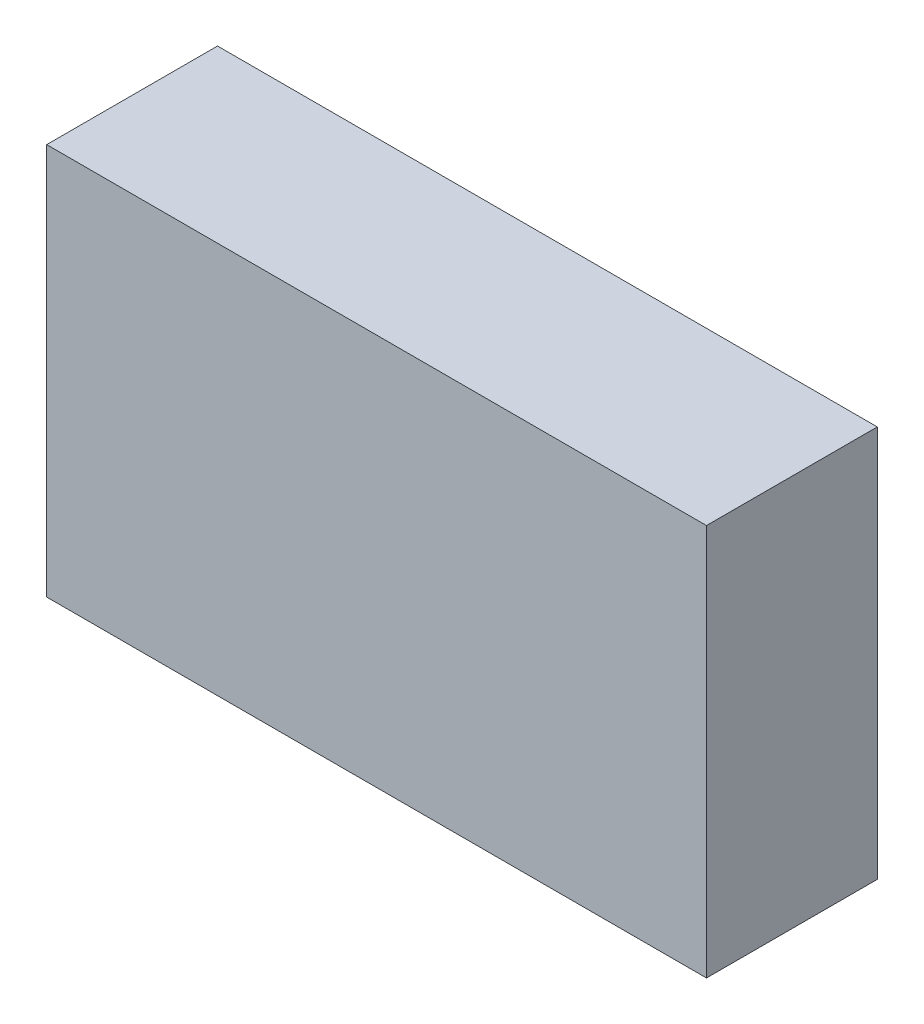
SolidWorks part; units mm, degrees
ref_plane "Front Plane" through (0, 0, 0) normal (0, 0, 1) x (1, 0, 0)
ref_plane "Top Plane" through (0, 0, 0) normal (0, 1, 0) x (1, 0, 0)
ref_plane "Right Plane" through (0, 0, 0) normal (1, 0, 0) x (0, 0, -1)
sketch "Sketch1" plane through (0, 0, 0) normal (0, 0, 1) x (1, 0, 0)
  line L1 (0, 0) -> (19.7, 0)
  line L2 (0, 0) -> (0, 11.7)
  line L3 (0, 11.7) -> (19.7, 11.7)
  line L4 (19.7, 0) -> (19.7, 11.7)
extrude "Boss-Extrude1" add sketch "Sketch1" along normal blind 5.1
